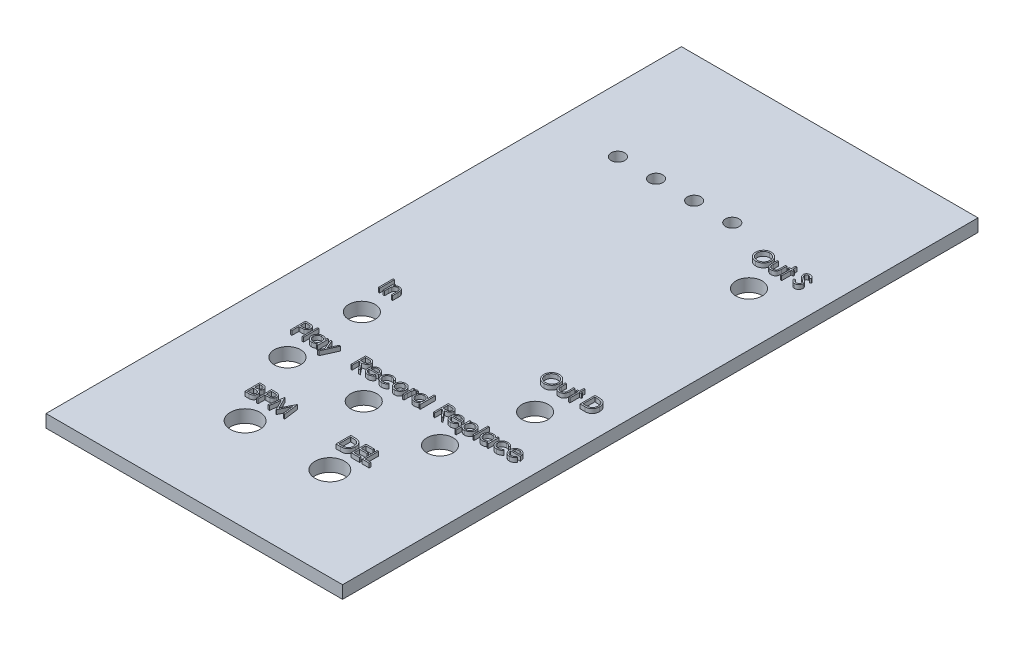
SolidWorks part; units mm, degrees
ref_plane "Front Plane" through (0, 0, 0) normal (0, 0, 1) x (1, 0, 0)
ref_plane "Top Plane" through (0, 0, 0) normal (0, 1, 0) x (1, 0, 0)
ref_plane "Right Plane" through (0, 0, 0) normal (1, 0, 0) x (0, 0, -1)
sketch "Sketch1" plane through (0, 0, 0) normal (0, 1, 0) x (1, 0, 0)
  line L0 (1.4373, -30) -> (50001.4373, -30) construction
  line L1 (0, 0) -> (70, 0)
  line L2 (0, 0) -> (0, -150)
  line L3 (0, -150) -> (70, -150)
  line L4 (70, 0) -> (70, -150)
  line L5 (0, -91.96) -> (50000, -91.96) construction
  line L6 (57.41, -12.0961) -> (57.41, -50012.0961) construction
  line L7 (0, -110) -> (70, -110) construction
  line L8 (0, -128) -> (50000, -128) construction
  circle A0 centre (15, -30) radius 1.6
  circle A1 centre (24, -30) radius 1.6
  circle A2 centre (33, -30) radius 1.6
  circle A3 centre (42, -30) radius 1.6
  circle A4 centre (16.52, -91.96) radius 3.1
  circle A5 centre (57.41, -91.96) radius 3.1
  circle A6 centre (57.41, -41.46) radius 3.1
  circle A7 centre (17, -110) radius 3.1
  circle A8 centre (35, -110) radius 3.1
  circle A9 centre (53, -110) radius 3.1
  circle A12 centre (25, -128) radius 3.5
  circle A13 centre (45, -128) radius 3.5
  dimension "D2" = 3.2
  dimension "D3" = 9
  dimension "D4" = 9
  dimension "D5" = 9
  dimension "D6" = 15
  dimension "D7" = 6.2
  dimension "D8" = 40.89
  dimension "D9" = 50.5
  dimension "D10" = 15.41
  dimension "D14" = 6.2
  dimension "D19" = 22
  dimension "D20" = 7
  dimension "D21" = 20
  dimension "D22" = 25
  dimension "D1" = 150
  dimension "D11" = 11.46
  dimension "D12" = 70
  dimension "D13" = 30
  dimension "D15" = 40
  dimension "D16" = 17
  dimension "D17" = 18
  dimension "D18" = 18
extrude "Boss-Extrude1" add sketch "Sketch1" along normal blind 3
sketch "Sketch2" plane through (0, 3, 0) normal (0, 1, 0) x (1, 0, 0)
  line L0 (70, -150) -> (70, 0) construction
  line L1 (70, 0) -> (0, 0) construction
  line L2 (0, 0) -> (0, -150) construction
  line L3 (0, -150) -> (70, -150) construction
  text T0 "Out S"
  text T1 "In"
  text T2 "Out D"
  text T3 "Play\r\n"
  text T4 "Record\r\n"
  text T5 "Replace"
  text T6 "BPM"
  text T7 "DEL"
  point P1 (54.31, -34.5622)
  point P7 (12.0019, -85.053)
  point P13 (51.5, -86)
  point P15 (9.7094, -106.5538)
  point P17 (27.6003, -106.9)
  point P19 (48.7904, -105)
  point P21 (12.3, -123.1179)
  point P23 (42.4975, -123)
  dimension "D1" = 18.5
  dimension "D2" = 36
  dimension "D3" = 14
  dimension "D4" = 64
  dimension "D5" = 18.5
  dimension "D6" = 64
  dimension "D7" = 12.3
  dimension "D8" = 45
  dimension "D9" = 26.5
  dimension "D10" = 45
  dimension "D11" = 45
  dimension "D12" = 46
  dimension "D13" = 19.5
  dimension "D14" = 27
  dimension "D15" = 27
  dimension "D16" = 29
extrude "Boss-Extrude2" add sketch "Sketch2" along normal blind 1
